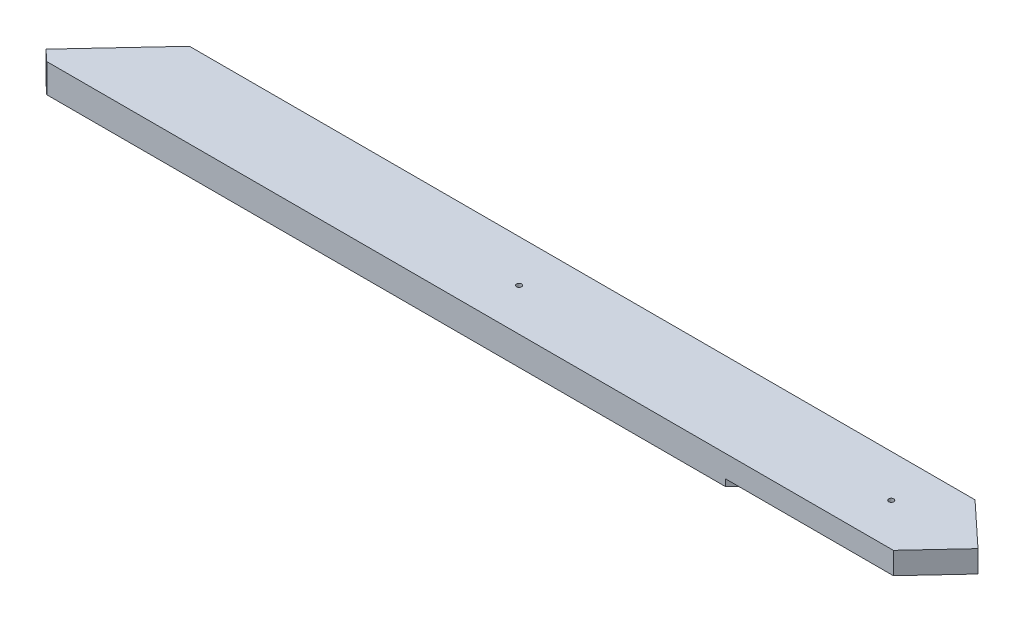
SolidWorks part; units mm, degrees
material "Pine"
ref_plane "Front Plane" through (0, 0, 0) normal (0, 0, 1) x (1, 0, 0)
ref_plane "Top Plane" through (0, 0, 0) normal (0, 1, 0) x (1, 0, 0)
ref_plane "Right Plane" through (0, 0, 0) normal (1, 0, 0) x (0, 0, -1)
sketch "Sketch1" plane through (0, 0, 0) normal (0, 1, 0) x (1, 0, 0)
  line L1 (-550, 50) -> (550, 50)
  line L2 (-550, 50) -> (-550, -50)
  line L3 (-550, -50) -> (550, -50)
  line L4 (550, 50) -> (550, -50)
  line L5 (-550, 50) -> (550, -50) construction
  line L6 (-550, -50) -> (550, 50) construction
  point P0 (0, 0)
  dimension "D1" = 1100
  dimension "D2" = 100
extrude "Boss-Extrude1" add sketch "Sketch1" along normal blind 34
sketch "Sketch2" plane through (0, 34, 0) normal (0, 1, 0) x (1, 0, 0)
  circle A0 centre (0, 0) radius 3
extrude "Cut-Extrude1" cut sketch "Sketch2" against normal through all
pattern_linear "LPattern1" count 2 spacing 440 along (1, 0, 0) of "Cut-Extrude1"
sketch "Sketch3" plane through (0, 34, 0) normal (0, 1, 0) x (1, 0, 0)
  line L0 (540.7626, 1.7747) -> (414.9075, 119.0785)
  line L1 (414.9075, 119.0785) -> (523.8856, 236.0009)
  line L2 (523.8856, 236.0009) -> (780.8085, 33.3558)
  line L3 (780.8085, 33.3558) -> (490.2865, -251.9026)
  line L4 (490.2865, -251.9026) -> (394.8833, -154.739)
  line L5 (394.8833, -154.739) -> (540.7626, 1.7747)
  line L6 (492.5057, -50) -> (36.2171, -539.5513) construction
  line L7 (489.0217, 50) -> (540.7626, 1.7747) construction
extrude "Cut-Extrude2" cut sketch "Sketch3" against normal through all
sketch "Sketch4" plane through (0, 0, 0) normal (0, -1, 0) x (1, 0, 0)
  line L0 (-439.5489, -50) -> (-521.3671, 37.7826)
  line L1 (-521.3671, 37.7826) -> (-461.555, 93.5307)
  line L2 (-461.555, 93.5307) -> (-639.5661, 284.5186)
  line L3 (-639.5661, 284.5186) -> (-887.9644, 45.984)
  line L4 (-887.9644, 45.984) -> (-622.186, -220.2277)
  line L5 (-622.186, -220.2277) -> (-439.5489, -50)
  line L6 (-613.334, 136.4538) -> (68.4842, -595.0679) construction
  line L7 (489.0217, -50) -> (-550, -50) construction
  dimension "D1" = 120
extrude "Cut-Extrude3" cut sketch "Sketch4" against normal through all
sketch "Sketch5" plane through (0, 0, 0) normal (0, -1, 0) x (1, 0, 0)
  line L0 (457.6591, -125.2797) -> (196.6736, 154.7312)
  line L1 (196.6736, 154.7312) -> (458.2732, 338.877)
  line L2 (458.2732, 338.877) -> (810.6589, -71.0728)
  line L3 (810.6589, -71.0728) -> (457.6591, -125.2797)
  line L4 (70.5497, 290.0494) -> (387.4943, -50) construction
extrude "Cut-Extrude4" cut sketch "Sketch5" against normal blind 8
equation "\"noga\"=440"
equation "\"D3@LPattern1\"=\"noga\""
